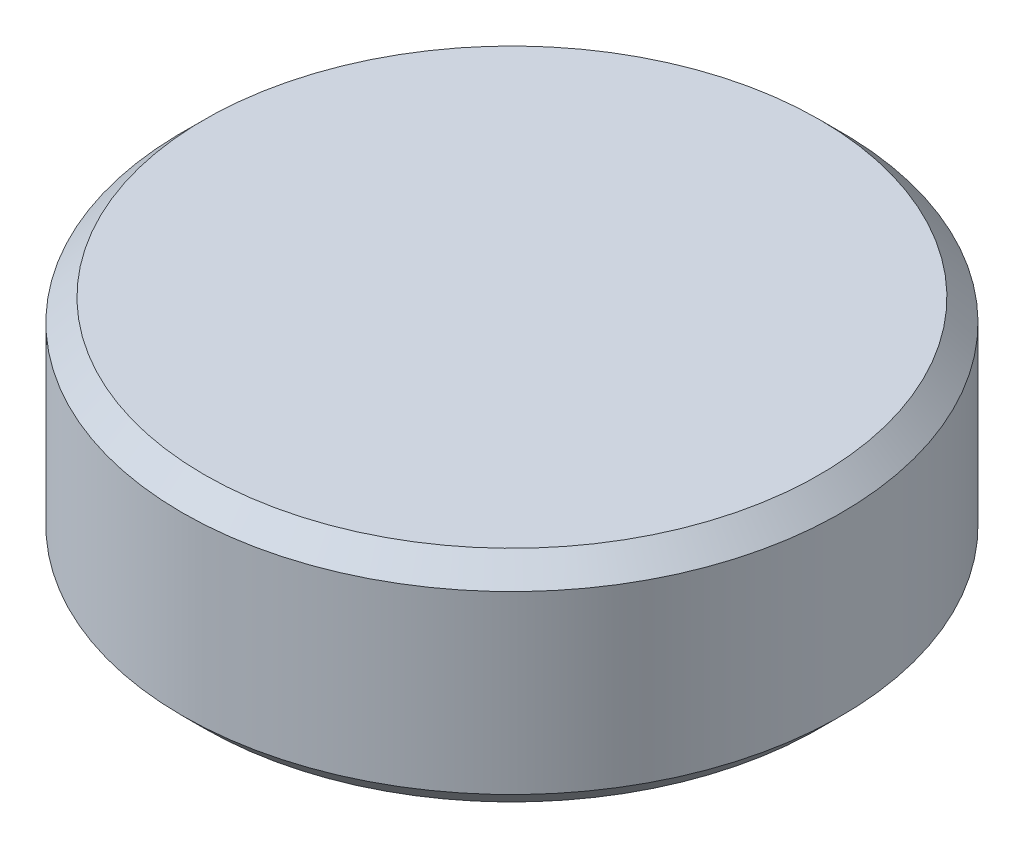
SolidWorks part; units mm, degrees
ref_plane "Спереди" through (0, 0, 0) normal (0, 0, 1) x (1, 0, 0)
ref_plane "Сверху" through (0, 0, 0) normal (0, 1, 0) x (1, 0, 0)
ref_plane "Справа" through (0, 0, 0) normal (1, 0, 0) x (0, 0, -1)
sketch "Эскиз1" plane through (0, 0, 0) normal (0, 1, 0) x (1, 0, 0)
  circle A0 centre (0, 0) radius 30
  dimension "D1" = 60
extrude "Бобышка-Вытянуть1" add sketch "Эскиз1" along normal blind 20
chamfer "Фаска1" distance 2 angle 45 2 edges at (0, 0, 30) (0, 20, 30)
